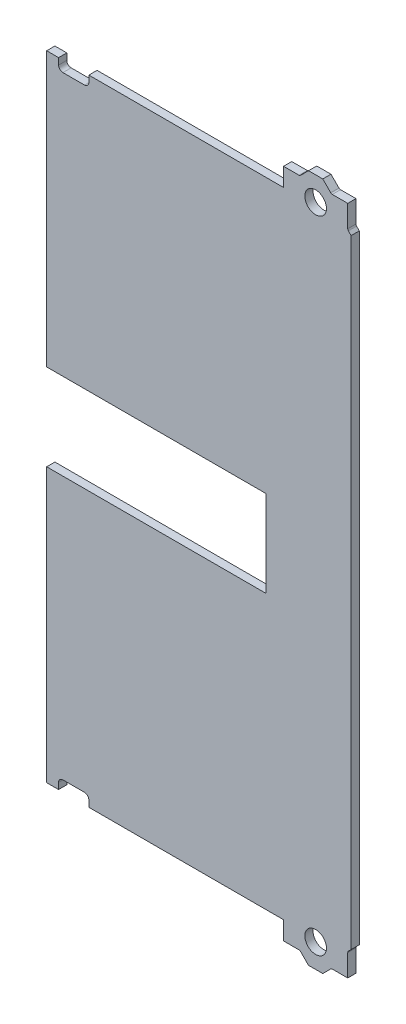
SolidWorks part; units mm, degrees
ref_plane "Front Plane" through (0, 0, 0) normal (0, 0, 1) x (1, 0, 0)
ref_plane "Top Plane" through (0, 0, 0) normal (0, 1, 0) x (1, 0, 0)
ref_plane "Right Plane" through (0, 0, 0) normal (1, 0, 0) x (0, 0, -1)
sketch "Sketch1" plane through (0, 0, 0) normal (0, 0, 1) x (1, 0, 0)
  line L31 (16.4, -92.1487) -> (-22.8779, -92.1487) construction
  line L65 (-124.4348, -238.7398) -> (-118.9347, -238.7398)
  line L66 (-118.9347, -238.7398) -> (-118.9347, -235.8487)
  line L67 (-116.9347, -233.8487) -> (-106.9348, -233.8487)
  line L107 (-140.5566, -92.1487) -> (-1273.406, -92.1487) construction
  line L109 (-104.9348, -238.8487) -> (-104.9348, -235.8487)
  line L118 (-124.4348, -72.1487) -> (-22.8779, -72.1487)
  line L120 (-124.4348, -112.1487) -> (-124.4348, -238.7398)
  line L121 (-124.4348, -112.1487) -> (-22.8779, -112.1487)
  line L122 (-22.8779, -72.1487) -> (-22.8779, -112.1487)
  line L123 (-86.8442, -112.1487) -> (-86.8442, -95.8016) construction
  line L124 (-104.9348, -238.8487) -> (-14.85, -238.8487)
  line L140 (-7.7071, 63.0513) -> (-14.85, 63.0513)
  line L141 (-14.85, 63.0513) -> (-14.85, 54.5513)
  line L151 (-14.85, -238.8487) -> (-14.85, -247.3487)
  line L152 (-14.85, -247.3487) -> (-7.7071, -247.3487)
  line L153 (-7, -247.6416) -> (-3.2929, -251.3487)
  line L154 (-3.2929, -251.3487) -> (3.2929, -251.3487)
  line L155 (3.2929, -251.3487) -> (7, -247.6416)
  line L156 (7.7071, -247.3487) -> (14.85, -247.3487)
  line L157 (14.85, -247.3487) -> (14.85, -237.1558)
  line L158 (15.1429, -236.4487) -> (16.4, -235.1916)
  line L165 (16.4, -235.1916) -> (16.4, 50.8942)
  line L166 (16.4, 50.8942) -> (15.1429, 52.1513)
  line L167 (14.85, 52.8584) -> (14.85, 63.0513)
  line L168 (14.85, 63.0513) -> (7.7071, 63.0513)
  line L169 (7, 63.3442) -> (3.2929, 67.0513)
  line L170 (3.2929, 67.0513) -> (-3.2929, 67.0513)
  line L171 (-3.2929, 67.0513) -> (-7, 63.3442)
  line L172 (-118.9348, 51.5513) -> (-118.9348, 54.5513)
  line L173 (-118.9348, 54.5513) -> (-124.4348, 54.5513)
  line L174 (-124.4348, 54.5513) -> (-124.4348, -72.1487)
  line L177 (-14.85, 54.5513) -> (-104.9348, 54.5513)
  line L178 (-104.9348, 54.5513) -> (-104.9348, 51.5513)
  line L179 (-106.9348, 49.5513) -> (-116.9348, 49.5513)
  arc A30 (-116.9347, -233.8487) -> (-118.9347, -235.8487) centre (-116.9347, -235.8487) ccw
  arc A31 (-104.9348, -235.8487) -> (-106.9348, -233.8487) centre (-106.9348, -235.8487) ccw
  circle A33 centre (0, -240.3353) radius 5
  circle A34 centre (0, 56.0378) radius 5
  arc A42 (-7.7071, 63.0513) -> (-7, 63.3442) centre (-7.7071, 64.0513) ccw
  arc A45 (-7, -247.6416) -> (-7.7071, -247.3487) centre (-7.7071, -248.3487) ccw
  arc A46 (7.7071, -247.3487) -> (7, -247.6416) centre (7.7071, -248.3487) ccw
  arc A47 (15.1429, -236.4487) -> (14.85, -237.1558) centre (15.85, -237.1558) ccw
  arc A52 (14.85, 52.8584) -> (15.1429, 52.1513) centre (15.85, 52.8584) ccw
  arc A53 (7, 63.3442) -> (7.7071, 63.0513) centre (7.7071, 64.0513) ccw
  arc A54 (-118.9348, 51.5513) -> (-116.9348, 49.5513) centre (-116.9348, 51.5513) ccw
  arc A55 (-106.9348, 49.5513) -> (-104.9348, 51.5513) centre (-106.9348, 51.5513) ccw
  point P21 (-22.8779, -92.1487)
  point P79 (-65.8112, -233.8487)
  dimension "D1" = 2
  dimension "D5" = 318.4
  dimension "D10" = 2
  dimension "D14" = 2
  dimension "D8" = 2
  dimension "D11" = 3
  dimension "D2" = 40
  dimension "D12" = 5.5
  dimension "D15" = 2
  dimension "D3" = 286.0858
  dimension "D6" = 2
  dimension "D7" = 5.5001
  dimension "D9" = 9.9999
  dimension "D13" = 10
  dimension "D16" = 3
  dimension "D17" = 3
  dimension "D18" = 2
  dimension "D19" = 293.2911
  dimension "D20" = 37.5906
extrude "Boss-Extrude1" add sketch "Sketch1" along normal blind 3.8
